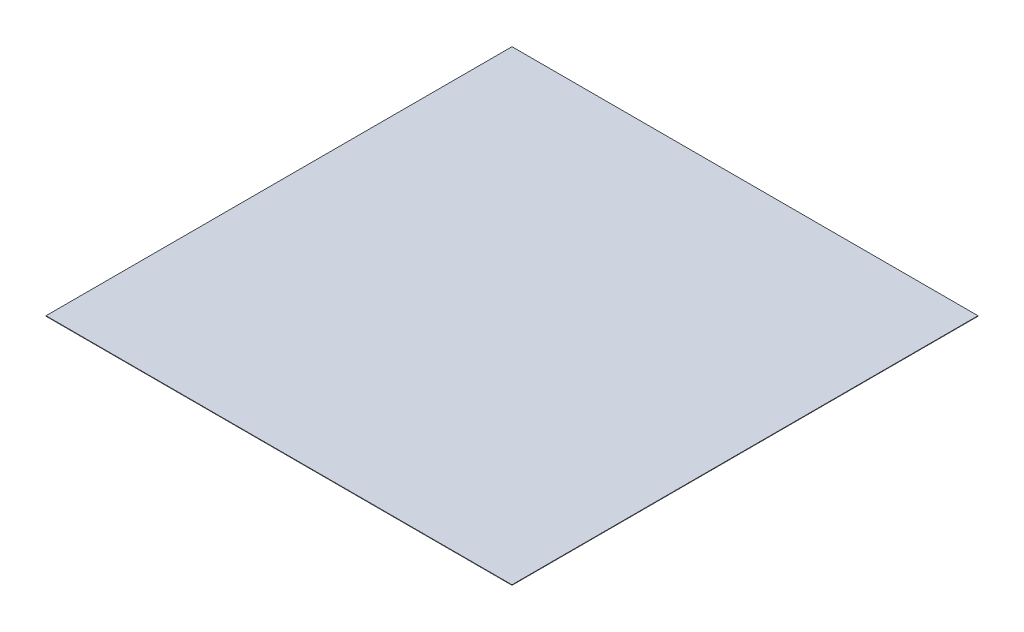
SolidWorks part; units mm, degrees
ref_plane "Front Plane" through (0, 0, 0) normal (0, 0, 1) x (1, 0, 0)
ref_plane "Top Plane" through (0, 0, 0) normal (0, 1, 0) x (1, 0, 0)
ref_plane "Right Plane" through (0, 0, 0) normal (1, 0, 0) x (0, 0, -1)
sketch "Sketch1" plane through (0, 0, 0) normal (0, 1, 0) x (1, 0, 0)
  line L1 (-5000, 5000) -> (5000, 5000)
  line L2 (-5000, 5000) -> (-5000, -5000)
  line L3 (-5000, -5000) -> (5000, -5000)
  line L4 (5000, 5000) -> (5000, -5000)
  line L5 (-5000, 5000) -> (5000, -5000) construction
  line L6 (-5000, -5000) -> (5000, 5000) construction
  point P0 (0, 0)
  dimension "D1" = 10000
  dimension "D2" = 10000
extrude "Boss-Extrude1" add sketch "Sketch1" against normal blind 10
